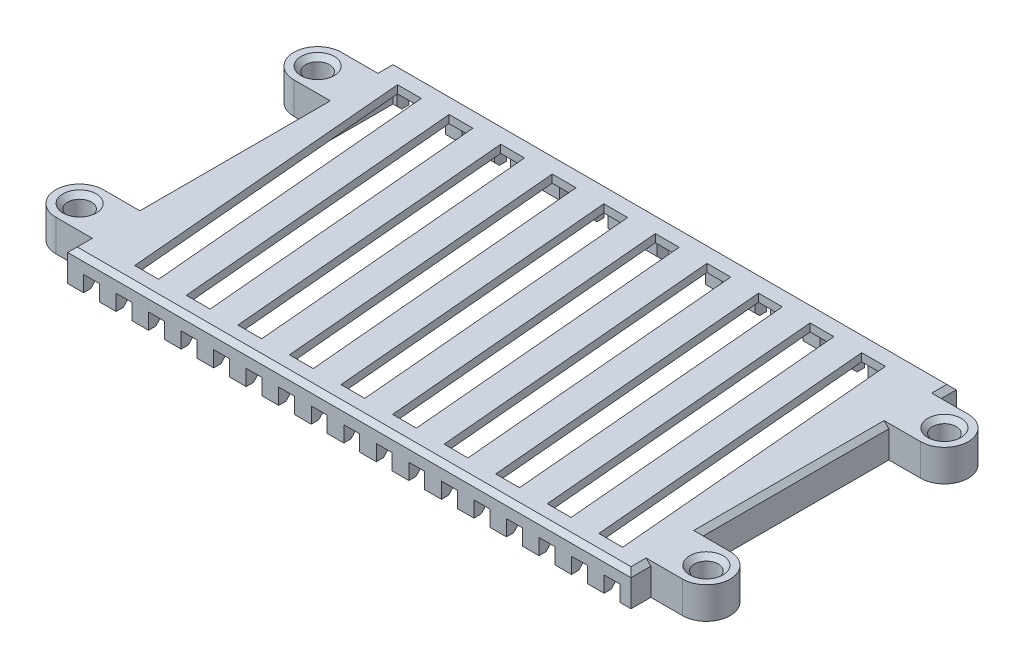
SolidWorks part; units mm, degrees
ref_plane "前视基准面" through (0, 0, 0) normal (0, 0, 1) x (1, 0, 0)
ref_plane "上视基准面" through (0, 0, 0) normal (0, 1, 0) x (1, 0, 0)
ref_plane "右视基准面" through (0, 0, 0) normal (1, 0, 0) x (0, 0, -1)
other "Configuration Table"
sketch "草图1" plane through (0, 0, 0) normal (0, 1, 0) x (1, 0, 0)
  line L0 (0, 35.4779) -> (0, -35.3561) construction
  line L1 (-47.5, 31) -> (-41.5, 31)
  line L2 (-47.5, 25) -> (-47.5, -25)
  line L3 (-47.5, -31) -> (-41.5, -31)
  line L4 (47.5, 25) -> (47.5, -25)
  line L5 (-47.5, 31) -> (47.5, -31) construction
  line L6 (-47.5, -31) -> (47.5, 31) construction
  line L9 (-41.5, 31) -> (-41.5, 41)
  line L11 (-29.5, 31) -> (-29.5, 41)
  line L12 (29.5, 31) -> (29.5, 41)
  line L14 (41.5, 31) -> (41.5, 41)
  line L15 (-78.7463, 0) -> (58.6748, 0) construction
  line L16 (41.5, -31) -> (41.5, -41)
  line L18 (29.5, -31) -> (29.5, -41)
  line L21 (-29.5, -31) -> (-29.5, -41)
  line L23 (-41.5, -31) -> (-41.5, -41)
  line L24 (-29.5, 31) -> (-3, 31)
  line L25 (41.5, 31) -> (47.5, 31)
  line L26 (41.5, -31) -> (47.5, -31)
  line L27 (-29.5, -31) -> (-3, -31)
  line L28 (47.5, 31) -> (50.8, 31)
  line L29 (-47.5, 31) -> (-50.8, 31)
  line L31 (-47.5, 25) -> (-50.8, 25)
  line L33 (47.5, 25) -> (50.8, 25)
  line L36 (47.5, -25) -> (50.8, -25)
  line L37 (47.5, -31) -> (50.8, -31)
  line L38 (-47.5, -31) -> (-50.8, -31)
  line L39 (-47.5, -25) -> (-50.8, -25)
  line L41 (-3, -33.8) -> (-3, -31)
  line L43 (-3, 33.8) -> (-3, 31)
  line L45 (3, 33.8) -> (3, 31)
  line L47 (3, -33.8) -> (3, -31)
  line L48 (3, 31) -> (29.5, 31)
  line L49 (3, -31) -> (29.5, -31)
  arc A0 (-41.5, 41) -> (-29.5, 41) centre (-35.5, 41) cw
  arc A1 (-41.5, -41) -> (-29.5, -41) centre (-35.5, -41) ccw
  arc A2 (41.5, -41) -> (29.5, -41) centre (35.5, -41) cw
  arc A3 (41.5, 41) -> (29.5, 41) centre (35.5, 41) ccw
  arc A4 (-50.8, 31) -> (-50.8, 25) centre (-50.8, 28) ccw
  circle A5 centre (-50.8, 28) radius 1.5
  circle A6 centre (50.8, 28) radius 1.5
  arc A7 (50.8, 31) -> (50.8, 25) centre (50.8, 28) cw
  circle A8 centre (50.8, -28) radius 1.5
  arc A9 (50.8, -31) -> (50.8, -25) centre (50.8, -28) ccw
  circle A10 centre (-50.8, -28) radius 1.5
  arc A11 (-50.8, -31) -> (-50.8, -25) centre (-50.8, -28) cw
  arc A12 (-3, 33.8) -> (3, 33.8) centre (0, 33.8) cw
  circle A13 centre (0, 33.8) radius 1.5
  circle A14 centre (0, -33.8) radius 1.5
  arc A15 (-3, -33.8) -> (3, -33.8) centre (0, -33.8) ccw
  point P0 (0, 0)
  dimension "D8" = 2.8
  dimension "D1" = 95
  dimension "D2" = 62
  dimension "D3" = 83
  dimension "D4" = 12
  dimension "D5" = 10
  dimension "D6" = 3.3
  dimension "D7" = 6
  dimension "D9" = 6
extrude "凸台-拉伸1" add sketch "草图1" against normal blind 15
sketch "草图2" plane through (0, -15, 0) normal (0, -1, 0) x (1, 0, 0)
  line L0 (-63.1336, 0) -> (63.5579, 0) construction
  line L1 (-57.0239, 31) -> (-3, 31)
  line L2 (-57.0239, 31) -> (-57.0239, 48.5806)
  line L3 (-57.0239, 48.5806) -> (57.0239, 48.5806)
  line L4 (57.0239, 31) -> (57.0239, 48.5806)
  line L5 (0, 56.9992) -> (0, -44.1169) construction
  line L6 (3, 33.8) -> (3, 31) construction
  line L7 (-3, 31) -> (-3, 33.8) construction
  line L8 (3, 33.8) -> (3, 31)
  line L9 (-3, 31) -> (-3, 33.8)
  line L10 (3, 31) -> (57.0239, 31)
  line L11 (3, -33.8) -> (3, -31)
  line L12 (-3, -31) -> (-3, -33.8)
  line L13 (-57.0239, -31) -> (-3, -31)
  line L14 (-57.0239, -31) -> (-57.0239, -48.5806)
  line L15 (-57.0239, -48.5806) -> (57.0239, -48.5806)
  line L16 (57.0239, -31) -> (57.0239, -48.5806)
  line L17 (3, -31) -> (57.0239, -31)
  arc A0 (3, 33.8) -> (-3, 33.8) centre (0, 33.8) ccw construction
  arc A1 (3, 33.8) -> (-3, 33.8) centre (0, 33.8) ccw
  arc A2 (3, -33.8) -> (-3, -33.8) centre (0, -33.8) cw
extrude "切除-拉伸1" cut sketch "草图2" against normal blind 11
sketch "草图3" plane through (0, -15, 0) normal (0, -1, 0) x (1, 0, 0)
  line L0 (47.5, 25) -> (47.5, -25) construction
  line L1 (-45, -28.5) -> (45, -28.5)
  line L2 (-45, -28.5) -> (-45, 28.5)
  line L3 (-45, 28.5) -> (45, 28.5)
  line L4 (45, -28.5) -> (45, 28.5)
  line L5 (-45, -28.5) -> (45, 28.5) construction
  line L6 (-45, 28.5) -> (45, -28.5) construction
  line L7 (-50.8, 31) -> (-3, 31) construction
  point P0 (0, 0)
  dimension "D1" = 2.5
  dimension "D2" = 2.5
extrude "切除-拉伸2" cut sketch "草图3" against normal blind 12
sketch "草图4" plane through (0, -4, 0) normal (0, -1, 0) x (1, 0, 0)
  line L0 (-29.5, 41) -> (-41.5, 41) construction
  line L1 (-71.7869, 0) -> (71.1524, 0) construction
  line L2 (0, 61.1393) -> (0, -47.8922) construction
  circle A0 centre (-35.5, 41) radius 2.8
  circle A1 centre (35.5, 41) radius 2.8
  circle A2 centre (35.5, -41) radius 2.8
  circle A3 centre (-35.5, -41) radius 2.8
extrude "凸台-拉伸2" add sketch "草图4" along normal blind 3.3 separate body
sketch "草图5" plane through (0, -7.3, 0) normal (0, -1, 0) x (1, 0, 0)
  line L0 (-58.868, 0) -> (56.1189, 0) construction
  line L1 (0, 46.5823) -> (0, -51.4835) construction
  circle A0 centre (-35.5, 41) radius 1.5
  circle A1 centre (35.5, 41) radius 1.5
  circle A2 centre (35.5, -41) radius 1.5
  circle A3 centre (-35.5, -41) radius 1.5
extrude "凸台-拉伸3" add sketch "草图5" along normal blind 1.3 separate body
sketch "草图6" plane through (0, -15, 0) normal (0, -1, 0) x (1, 0, 0)
  line L0 (-50.8, 31) -> (-3, 31) construction
  line L1 (-47.5, 31) -> (47.5, 31)
  line L2 (-47.5, 31) -> (-47.5, -31)
  line L3 (-47.5, -31) -> (47.5, -31)
  line L4 (47.5, 31) -> (47.5, -31)
  line L5 (50.8, -31) -> (3, -31) construction
extrude "切除-拉伸3" cut sketch "草图6" against normal blind 5
sketch "草图7" plane through (0, -3, 0) normal (0, -1, 0) x (1, 0, 0)
  line L0 (-60.2485, 0) -> (64.067, 0) construction
  line L1 (0, 41.3678) -> (0, -47.8169) construction
  line L2 (-30, -23) -> (30, -23)
  line L3 (-30, 25) -> (-2, 25)
  line L4 (-30, 25) -> (-30, 23)
  line L5 (-30, 23) -> (30, 23)
  line L6 (30, 25) -> (30, 23)
  line L7 (-30, 25) -> (30, 23) construction
  line L8 (-30, 23) -> (30, 25) construction
  line L9 (30, -25) -> (30, -23)
  line L10 (-30, -25) -> (-2, -25)
  line L11 (-30, -25) -> (-30, -23)
  line L12 (45, 28.5) -> (-45, 28.5) construction
  line L13 (-2, 28.5) -> (2, 28.5)
  line L14 (-2, 28.5) -> (-2, 25)
  line L16 (2, 28.5) -> (2, 25)
  line L18 (2, -28.5) -> (2, -25)
  line L19 (-2, -28.5) -> (2, -28.5)
  line L20 (-2, -28.5) -> (-2, -25)
  line L21 (2, 25) -> (30, 25)
  line L22 (2, -25) -> (30, -25)
  line L23 (-45, -28.5) -> (-45, 28.5) construction
  line L24 (-42, 10) -> (-40, 10)
  line L25 (-42, 10) -> (-42, 2)
  line L26 (-42, -10) -> (-40, -10)
  line L27 (-40, 10) -> (-40, -10)
  line L28 (-42, 10) -> (-40, -10) construction
  line L29 (-42, -10) -> (-40, 10) construction
  line L30 (-42, -2) -> (-42, -10)
  line L31 (-45, 2) -> (-42, 2)
  line L32 (-45, 2) -> (-45, -2)
  line L33 (-45, -2) -> (-42, -2)
  line L35 (45, -2) -> (42, -2)
  line L36 (45, 2) -> (45, -2)
  line L37 (45, 2) -> (42, 2)
  line L38 (42, 10) -> (42, 2)
  line L39 (42, 10) -> (40, 10)
  line L40 (40, 10) -> (40, -10)
  line L41 (42, -10) -> (40, -10)
  line L42 (42, -2) -> (42, -10)
  point P5 (0, 24)
  point P24 (-41, 0)
  dimension "D1" = 23
  dimension "D2" = 2
  dimension "D3" = 60
  dimension "D4" = 4
  dimension "D5" = 2
  dimension "D6" = 20
  dimension "D7" = 3
  dimension "D8" = 4
extrude "凸台-拉伸4" [suppressed] add sketch "草图7" along normal blind 2.5
sketch "草图9" plane through (0, -10, 0) normal (0, -1, 0) x (1, 0, 0)
  line L0 (-45, 28.5) -> (45, 28.5) construction
  line L1 (41.5, 31) -> (32, 31)
  line L2 (41.5, 31) -> (41.5, 28.5)
  line L3 (41.5, 28.5) -> (32, 28.5)
  line L4 (32, 31) -> (32, 28.5)
  dimension "D1" = 9.5
extrude "切除-拉伸4" cut sketch "草图9" against normal blind 5
sketch "草图10" plane through (0, 0, 0) normal (0, 1, 0) x (1, 0, 0)
  line L1 (-32, -19) -> (32, -19)
  line L2 (-34, -17) -> (-34, 17)
  line L3 (-32, 19) -> (32, 19)
  line L4 (34, -17) -> (34, 17)
  line L5 (-34, -19) -> (34, 19) construction
  line L6 (-34, 19) -> (34, -19) construction
  arc A0 (-32, -19) -> (-34, -17) centre (-32, -17) cw
  arc A1 (32, -19) -> (34, -17) centre (32, -17) ccw
  arc A2 (32, 19) -> (34, 17) centre (32, 17) cw
  arc A3 (-34, 17) -> (-32, 19) centre (-32, 17) cw
  point P0 (0, 0)
  dimension "D3" = 2
  dimension "D1" = 68
  dimension "D2" = 38
extrude "切除-拉伸5" cut sketch "草图10" against normal through all
fillet "圆角1" radius 3 8 edges at (41.5, -2, 31) (29.5, -2, 31) (-29.5, -2, 31) (-41.5, -2, 31) (-41.5, -2, -31) (-29.5, -2, -31) (29.5, -2, -31) (41.5, -2, -31)
fillet "圆角3" radius 1 12 edges at (0, -3, -28.5) (-45, -3, 0) (0, -3, 28.5) (45, -3, 0) (-33.4142, -3, -18.4142) (0, -3, -19) (33.4142, -3, -18.4142) (34, -3, 0) (33.4142, -3, 18.4142) (0, -3, 19) (-33.4142, -3, 18.4142) (-34, -3, 0)
combine bodies "组合1" operation type add bodies to combine 111 121 115 109 112 113 116 110 121 121 114
fillet "圆角4" [suppressed] radius 1
sketch "草图12" plane through (0, -3, 0) normal (0, -1, 0) x (1, 0, 0)
  line L0 (-57.3633, 0) -> (63.3882, 0) construction
  line L1 (-45, -28.5) -> (-45, 28.5) construction
  line L2 (0, 45.8091) -> (0, -49.9604) construction
  circle A0 centre (-39.5, 15) radius 2.5
  circle A1 centre (-39.5, -15) radius 2.5
  circle A2 centre (39.5, -15) radius 2.5
  circle A3 centre (39.5, 15) radius 2.5
  dimension "D1" = 5.5
  dimension "D2" = 15
extrude "凸台-拉伸5" add sketch "草图12" along normal blind 3
sketch "草图13" plane through (0, -6, 0) normal (0, -1, 0) x (1, 0, 0)
  circle A0 centre (-39.5, 15) radius 1.5
  circle A1 centre (39.5, 15) radius 2.5
  circle A2 centre (39.5, 15) radius 2.5
  circle A3 centre (39.5, -15) radius 2.5
  circle A4 centre (39.5, -15) radius 2.5
  circle A5 centre (-39.5, -15) radius 2.5
  circle A6 centre (-39.5, -15) radius 2.5
  circle A7 centre (-39.5, 15) radius 2.5
  circle A8 centre (-39.5, 15) radius 2.5
  circle A9 centre (39.5, 15) radius 1.5
  circle A10 centre (39.5, -15) radius 1.5
  circle A11 centre (-39.5, -15) radius 1.5
  dimension "D1" = 0
  dimension "D2" = 0
  dimension "D3" = 0
  dimension "D4" = 0
  dimension "D5" = 1
extrude "切除-拉伸6" cut sketch "草图13" against normal through all contours A10 | A9 | A11 | A0
chamfer "倒角1" distance 1 angle 45 4 edges at (-39.5, 0, 13.5) (39.5, 0, 13.5) (39.5, 0, -16.5) (-39.5, 0, -16.5)
sketch "草图14" plane through (0, -3, 0) normal (0, -1, 0) x (1, 0, 0)
  line L0 (8.25, 0) -> (-8.25, 0) construction
  line L1 (-42, 24) -> (-37, 24)
  line L2 (-42, 24) -> (-42, 20)
  line L3 (-42, 20) -> (-37, 20)
  line L4 (-37, 24) -> (-37, 20)
  line L5 (-42, 24) -> (-37, 20) construction
  line L6 (-42, 20) -> (-37, 24) construction
  line L7 (-42, -20) -> (-37, -20)
  line L8 (-37, -24) -> (-37, -20)
  line L9 (-42, -24) -> (-37, -24)
  line L10 (-42, -24) -> (-42, -20)
  line L11 (0, -8.25) -> (0, 8.25) construction
  line L12 (42, -24) -> (42, -20)
  line L13 (42, -24) -> (37, -24)
  line L14 (37, -24) -> (37, -20)
  line L15 (42, -20) -> (37, -20)
  line L16 (42, 20) -> (37, 20)
  line L17 (37, 24) -> (37, 20)
  line L18 (42, 24) -> (37, 24)
  line L19 (42, 24) -> (42, 20)
  point P0 (-39.5, 22)
  dimension "D1" = 22
  dimension "D2" = 5
  dimension "D3" = 4
extrude "切除-拉伸7" [suppressed] cut sketch "草图14" against normal through all
sketch "草图15" plane through (0, -3, 0) normal (0, -1, 0) x (1, 0, 0)
  line L0 (-45, 28.5) -> (32, 28.5) construction
  line L1 (-41, 25.5) -> (41, 25.5)
  line L2 (-41, 25.5) -> (-41, 21.5)
  line L3 (-41, 21.5) -> (41, 21.5)
  line L4 (41, 25.5) -> (41, 21.5)
  line L5 (-41, 25.5) -> (41, 21.5) construction
  line L6 (-41, 21.5) -> (41, 25.5) construction
  line L7 (8.25, 0) -> (-8.25, 0) construction
  line L8 (-41, -21.5) -> (41, -21.5)
  line L9 (41, -25.5) -> (41, -21.5)
  line L10 (-41, -25.5) -> (41, -25.5)
  line L11 (-41, -25.5) -> (-41, -21.5)
  line L12 (0, -8.25) -> (0, 8.25) construction
  line L13 (-40.75, 10) -> (-38.25, 10)
  line L14 (-40.75, 10) -> (-40.75, -10)
  line L15 (-40.75, -10) -> (-38.25, -10)
  line L16 (-38.25, 10) -> (-38.25, -10)
  line L17 (-40.75, 10) -> (-38.25, -10) construction
  line L18 (-40.75, -10) -> (-38.25, 10) construction
  line L19 (40.75, -10) -> (38.25, -10)
  line L20 (38.25, 10) -> (38.25, -10)
  line L21 (40.75, 10) -> (38.25, 10)
  line L22 (40.75, 10) -> (40.75, -10)
  point P0 (0, 23.5)
  point P5 (-39.5, 0)
  dimension "D1" = 4
  dimension "D2" = 5
  dimension "D3" = 82
  dimension "D4" = 2.5
  dimension "D5" = 20
extrude "切除-拉伸8" cut sketch "草图15" against normal through all
sketch "草图16" plane through (0, 0, 0) normal (0, 1, 0) x (1, 0, 0)
  line L0 (32, 19) -> (-32, 19) construction
  line L1 (-34, -19) -> (34, -19)
  line L2 (-34, -19) -> (-34, 19)
  line L3 (-34, 19) -> (34, 19)
  line L4 (34, -19) -> (34, 19)
  line L5 (-34, -19) -> (34, 19) construction
  line L6 (-34, 19) -> (34, -19) construction
  line L7 (34, -17) -> (34, 17) construction
  line L8 (-35.5, -20.5) -> (-35.5, 20.5)
  line L9 (-35.5, 20.5) -> (35.5, 20.5)
  line L10 (35.5, -20.5) -> (35.5, 20.5)
  line L11 (-35.5, -20.5) -> (35.5, -20.5)
  line L12 (-39.5, 18) -> (-35.5, 18)
  line L13 (-39.5, 12) -> (-35.5, 12)
  line L14 (-39.5, -12) -> (-35.5, -12)
  line L15 (-39.5, -18) -> (-35.5, -18)
  line L16 (39.5, 18) -> (35.5, 18)
  line L17 (39.5, 12) -> (35.5, 12)
  line L18 (39.5, -12) -> (35.5, -12)
  line L19 (39.5, -18) -> (35.5, -18)
  circle A0 centre (39.5, -15) radius 1.5 construction
  circle A1 centre (39.5, 15) radius 1.5 construction
  circle A2 centre (-39.5, -15) radius 1.5 construction
  circle A3 centre (-39.5, 15) radius 1.5 construction
  circle A4 centre (39.5, -15) radius 1.5
  circle A5 centre (39.5, 15) radius 1.5
  circle A6 centre (-39.5, -15) radius 1.5
  circle A7 centre (-39.5, 15) radius 1.5
  circle A8 centre (-39.5, 15) radius 3
  circle A9 centre (-39.5, -15) radius 3
  circle A10 centre (39.5, 15) radius 3
  circle A11 centre (39.5, -15) radius 3
  point P12 (0, 0)
  dimension "D1" = 0
  dimension "D2" = 1.5
  dimension "D3" = 1.5
extrude "凸台-拉伸6" add sketch "草图16" along normal blind 4 separate body contours A8 A7 | A9 A6 | A11 A4 | A10 A5 | L8 L11 L10 L9 L4 L1 L2 L3 | A8 L13 L8 L12 | A9 L15 L8 L14 | A10 L16 L10 L17 | A11 L18 L10 L19
sketch "草图17" plane through (0, 4, 0) normal (0, 1, 0) x (1, 0, 0)
  line L0 (34, -19) -> (34, 19) construction
  line L1 (-34, -19) -> (34, -19) construction
  line L2 (-34, -19) -> (-34, 19) construction
  line L3 (-34, 19) -> (34, 19) construction
  line L4 (34, -19) -> (34, 19)
  line L5 (-34, -19) -> (34, -19)
  line L6 (-34, -19) -> (-34, 19)
  line L7 (-34, 19) -> (34, 19)
extrude "凸台-拉伸7" add sketch "草图17" against normal blind 1
sketch "草图19" plane through (0, 0, 0) normal (0, 1, 0) x (1, 0, 0)
  line L1 (-63.5579, -53.1629) -> (63.5579, -53.1629)
  line L2 (-63.5579, -53.1629) -> (-63.5579, 53.1629)
  line L3 (-63.5579, 53.1629) -> (63.5579, 53.1629)
  line L4 (63.5579, -53.1629) -> (63.5579, 53.1629)
  line L5 (-63.5579, -53.1629) -> (63.5579, 53.1629) construction
  line L6 (-63.5579, 53.1629) -> (63.5579, -53.1629) construction
  point P0 (0, 0)
extrude "切除-拉伸9" cut sketch "草图19" against normal through all
sketch "草图21" plane through (0, 3, 0) normal (0, -1, 0) x (1, 0, 0)
  line L0 (-48.0013, 18.3015) -> (49.3338, 18.3015) construction
  line L1 (-44.5677, -18) -> (48.0382, -18) construction
  line L2 (-32.4273, -18) -> (-29.4273, -18)
  line L3 (-32.4273, -18) -> (-29.2513, 18.3015)
  line L4 (-29.4273, -18) -> (-26.2513, 18.3015)
  line L5 (-29.2513, 18.3015) -> (-26.2513, 18.3015)
  line L6 (-25.9273, -18) -> (-22.9273, -18)
  line L7 (-25.9273, -18) -> (-22.7513, 18.3015)
  line L8 (-22.7513, 18.3015) -> (-19.7513, 18.3015)
  line L9 (-22.9273, -18) -> (-19.7513, 18.3015)
  line L10 (-19.4273, -18) -> (-16.4273, -18)
  line L11 (-19.4273, -18) -> (-16.2513, 18.3015)
  line L12 (-16.2513, 18.3015) -> (-13.2513, 18.3015)
  line L13 (-16.4273, -18) -> (-13.2513, 18.3015)
  line L14 (-12.9273, -18) -> (-9.9273, -18)
  line L15 (-12.9273, -18) -> (-9.7513, 18.3015)
  line L16 (-9.7513, 18.3015) -> (-6.7513, 18.3015)
  line L17 (-9.9273, -18) -> (-6.7513, 18.3015)
  line L18 (-6.4273, -18) -> (-3.4273, -18)
  line L19 (-6.4273, -18) -> (-3.2513, 18.3015)
  line L20 (-3.2513, 18.3015) -> (-0.2513, 18.3015)
  line L21 (-3.4273, -18) -> (-0.2513, 18.3015)
  line L22 (0.0727, -18) -> (3.0727, -18)
  line L23 (0.0727, -18) -> (3.2487, 18.3015)
  line L24 (3.2487, 18.3015) -> (6.2487, 18.3015)
  line L25 (3.0727, -18) -> (6.2487, 18.3015)
  line L26 (6.5727, -18) -> (9.5727, -18)
  line L27 (6.5727, -18) -> (9.7487, 18.3015)
  line L28 (9.7487, 18.3015) -> (12.7487, 18.3015)
  line L29 (9.5727, -18) -> (12.7487, 18.3015)
  line L30 (13.0727, -18) -> (16.0727, -18)
  line L31 (13.0727, -18) -> (16.2487, 18.3015)
  line L32 (16.2487, 18.3015) -> (19.2487, 18.3015)
  line L33 (16.0727, -18) -> (19.2487, 18.3015)
  line L34 (19.5727, -18) -> (22.5727, -18)
  line L35 (19.5727, -18) -> (22.7487, 18.3015)
  line L36 (22.7487, 18.3015) -> (25.7487, 18.3015)
  line L37 (22.5727, -18) -> (25.7487, 18.3015)
  line L38 (26.0727, -18) -> (29.0727, -18)
  line L39 (26.0727, -18) -> (29.2487, 18.3015)
  line L40 (29.2487, 18.3015) -> (32.2487, 18.3015)
  line L41 (29.0727, -18) -> (32.2487, 18.3015)
  dimension "D1" = 3
  dimension "D2" = 85
  dimension "D3" = 10
extrude "切除-拉伸10" cut sketch "草图21" against normal through all
chamfer "倒角2" distance 0.6 angle 45 16 edges at (39.5, 4, -13.5) (-39.5, 4, -13.5) (-39.5, 4, 16.5) (39.5, 4, 16.5) (34, 0, 0) (0, 0, -19) (-34, 0, 0) (0, 0, 19) (35.5, 4, 0) (-35.5, 4, 0) (35.5, 4, -19.25) (-35.5, 4, -19.25) (0, 4, -20.5) (35.5, 4, 19.25) (-35.5, 4, 19.25) (0, 4, 20.5)
sketch "草图22" plane through (0, 0, -20.5) normal (0, 0, -1) x (-1, 0, 0)
  line L0 (35.5, 0) -> (-35.5, 0) construction
  line L1 (33.5, 0) -> (31.5, 0)
  line L2 (33.5, 0) -> (33.5, 2)
  line L3 (33.5, 2) -> (31.5, 2)
  line L4 (31.5, 0) -> (31.5, 2)
  line L5 (35.5, 3.4) -> (35.5, 0) construction
  line L6 (29.4, 0) -> (29.4, 2)
  line L7 (29.4, 0) -> (27.4, 0)
  line L8 (27.4, 0) -> (27.4, 2)
  line L9 (29.4, 2) -> (27.4, 2)
  line L10 (25.3, 0) -> (25.3, 2)
  line L11 (25.3, 0) -> (23.3, 0)
  line L12 (23.3, 0) -> (23.3, 2)
  line L13 (25.3, 2) -> (23.3, 2)
  line L14 (21.2, 0) -> (21.2, 2)
  line L15 (21.2, 0) -> (19.2, 0)
  line L16 (19.2, 0) -> (19.2, 2)
  line L17 (21.2, 2) -> (19.2, 2)
  line L18 (17.1, 0) -> (17.1, 2)
  line L19 (17.1, 0) -> (15.1, 0)
  line L20 (15.1, 0) -> (15.1, 2)
  line L21 (17.1, 2) -> (15.1, 2)
  line L22 (13, 0) -> (13, 2)
  line L23 (13, 0) -> (11, 0)
  line L24 (11, 0) -> (11, 2)
  line L25 (13, 2) -> (11, 2)
  line L26 (8.9, 0) -> (8.9, 2)
  line L27 (8.9, 0) -> (6.9, 0)
  line L28 (6.9, 0) -> (6.9, 2)
  line L29 (8.9, 2) -> (6.9, 2)
  line L30 (4.8, 0) -> (4.8, 2)
  line L31 (4.8, 0) -> (2.8, 0)
  line L32 (2.8, 0) -> (2.8, 2)
  line L33 (4.8, 2) -> (2.8, 2)
  line L34 (0.7, 0) -> (0.7, 2)
  line L35 (0.7, 0) -> (-1.3, 0)
  line L36 (-1.3, 0) -> (-1.3, 2)
  line L37 (0.7, 2) -> (-1.3, 2)
  line L38 (-3.4, 0) -> (-3.4, 2)
  line L39 (-3.4, 0) -> (-5.4, 0)
  line L40 (-5.4, 0) -> (-5.4, 2)
  line L41 (-3.4, 2) -> (-5.4, 2)
  line L42 (-7.5, 0) -> (-7.5, 2)
  line L43 (-7.5, 0) -> (-9.5, 0)
  line L44 (-9.5, 0) -> (-9.5, 2)
  line L45 (-7.5, 2) -> (-9.5, 2)
  line L46 (-11.6, 0) -> (-11.6, 2)
  line L47 (-11.6, 0) -> (-13.6, 0)
  line L48 (-13.6, 0) -> (-13.6, 2)
  line L49 (-11.6, 2) -> (-13.6, 2)
  line L50 (-15.7, 0) -> (-15.7, 2)
  line L51 (-15.7, 0) -> (-17.7, 0)
  line L52 (-17.7, 0) -> (-17.7, 2)
  line L53 (-15.7, 2) -> (-17.7, 2)
  line L54 (-19.8, 0) -> (-19.8, 2)
  line L55 (-19.8, 0) -> (-21.8, 0)
  line L56 (-21.8, 0) -> (-21.8, 2)
  line L57 (-19.8, 2) -> (-21.8, 2)
  line L58 (-23.9, 0) -> (-23.9, 2)
  line L59 (-23.9, 0) -> (-25.9, 0)
  line L60 (-25.9, 0) -> (-25.9, 2)
  line L61 (-23.9, 2) -> (-25.9, 2)
  line L62 (-28, 0) -> (-28, 2)
  line L63 (-28, 0) -> (-30, 0)
  line L64 (-30, 0) -> (-30, 2)
  line L65 (-28, 2) -> (-30, 2)
  line L66 (-32.1, 0) -> (-32.1, 2)
  line L67 (-32.1, 0) -> (-34.1, 0)
  line L68 (-34.1, 0) -> (-34.1, 2)
  line L69 (-32.1, 2) -> (-34.1, 2)
  dimension "D1" = 2
  dimension "D2" = 2
  dimension "D3" = 2
  dimension "D4" = 17
extrude "切除-拉伸11" cut sketch "草图22" against normal through all
